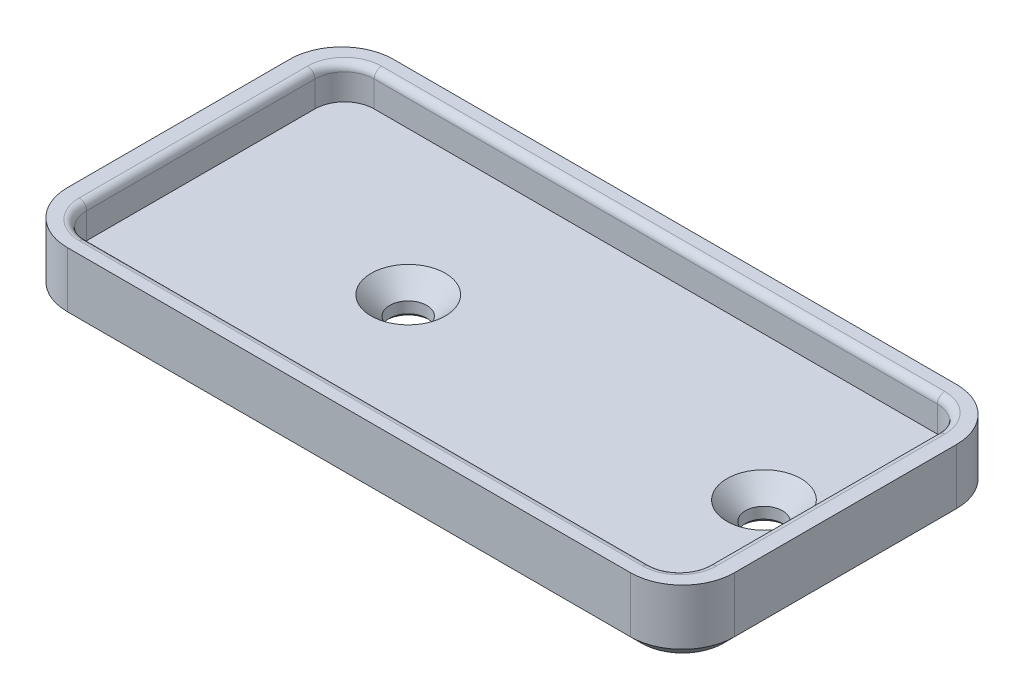
SolidWorks part; units mm, degrees
ref_plane "Спереди" through (0, 0, 0) normal (0, 0, 1) x (1, 0, 0)
ref_plane "Сверху" through (0, 0, 0) normal (0, 1, 0) x (1, 0, 0)
ref_plane "Справа" through (0, 0, 0) normal (1, 0, 0) x (0, 0, -1)
sketch "Эскиз1" plane through (0, 0, 0) normal (0, 1, 0) x (1, 0, 0)
  line L1 (-45, -22) -> (45, -22)
  line L2 (-45, -22) -> (-45, 22)
  line L3 (-45, 22) -> (45, 22)
  line L4 (45, -22) -> (45, 22)
  line L5 (0, 22) -> (0, -22) construction
  line L6 (-45, 0) -> (45, 0) construction
  point P0 (0, 0)
  dimension "D1" = 44
  dimension "D2" = 90
extrude "Бобышка-Вытянуть1" add sketch "Эскиз1" along normal blind 9
fillet "Скругление1" radius 7 4 edges at (-45, 4.5, -22) (-45, 4.5, 22) (45, 4.5, -22) (45, 4.5, 22)
sketch "Эскиз2" plane through (0, 9, 0) normal (0, 1, 0) x (1, 0, 0)
  line L1 (-42, -19.4) -> (42, -19.4)
  line L2 (-42, -19.4) -> (-42, 19.4)
  line L3 (-42, 19.4) -> (42, 19.4)
  line L4 (42, -19.4) -> (42, 19.4)
  line L5 (0, 19.4) -> (0, -19.4) construction
  line L6 (-42, 0) -> (42, 0) construction
  point P0 (0, 0)
  dimension "D1" = 84
  dimension "D2" = 38.8
extrude "Вырез-Вытянуть1" cut sketch "Эскиз2" against normal blind 4.5
sketch "Эскиз3" plane through (0, 4.5, 0) normal (0, 1, 0) x (1, 0, 0)
  line L0 (0, 15.7954) -> (0, 0) construction
  line L1 (0, 0) -> (50.7445, 0) construction
  line L2 (42, -19.4) -> (42, 19.4) construction
  circle A0 centre (34, 0) radius 2.5
  circle A1 centre (-14, 0) radius 2.5
  circle A2 centre (22, 0) radius 6.4675 construction
  dimension "D1" = 5
  dimension "D2" = 48
  dimension "D3" = 34
  dimension "D4" = 12
  dimension "D5" = 8
extrude "Вырез-Вытянуть2" cut sketch "Эскиз3" against normal blind 10
chamfer "Фаска1" distance 2.5 angle 45 2 edges at (-14, 4.5, -2.5) (34, 4.5, 2.5)
fillet "Скругление2" radius 4 4 edges at (-42, 6.75, 19.4) (42, 6.75, 19.4) (42, 6.75, -19.4) (-42, 6.75, -19.4)
fillet "Скругление3" radius 1 8 edges at (40.8284, 9, -18.2284) (42, 9, 0) (40.8284, 9, 18.2284) (0, 9, 19.4) (-40.8284, 9, 18.2284) (-42, 9, 0) (-40.8284, 9, -18.2284) (0, 9, -19.4)
fillet "Скругление4" radius 1.5 8 edges at (-42.9497, 0, 19.9497) (0, 0, 22) (42.9497, 0, 19.9497) (45, 0, 0) (42.9497, 0, -19.9497) (0, 0, -22) (-42.9497, 0, -19.9497) (-45, 0, 0) profile chamfer
chamfer "Фаска2" distance 0.5 angle 45 2 edges at (34, 0, -2.5) (-14, 0, -2.5)
